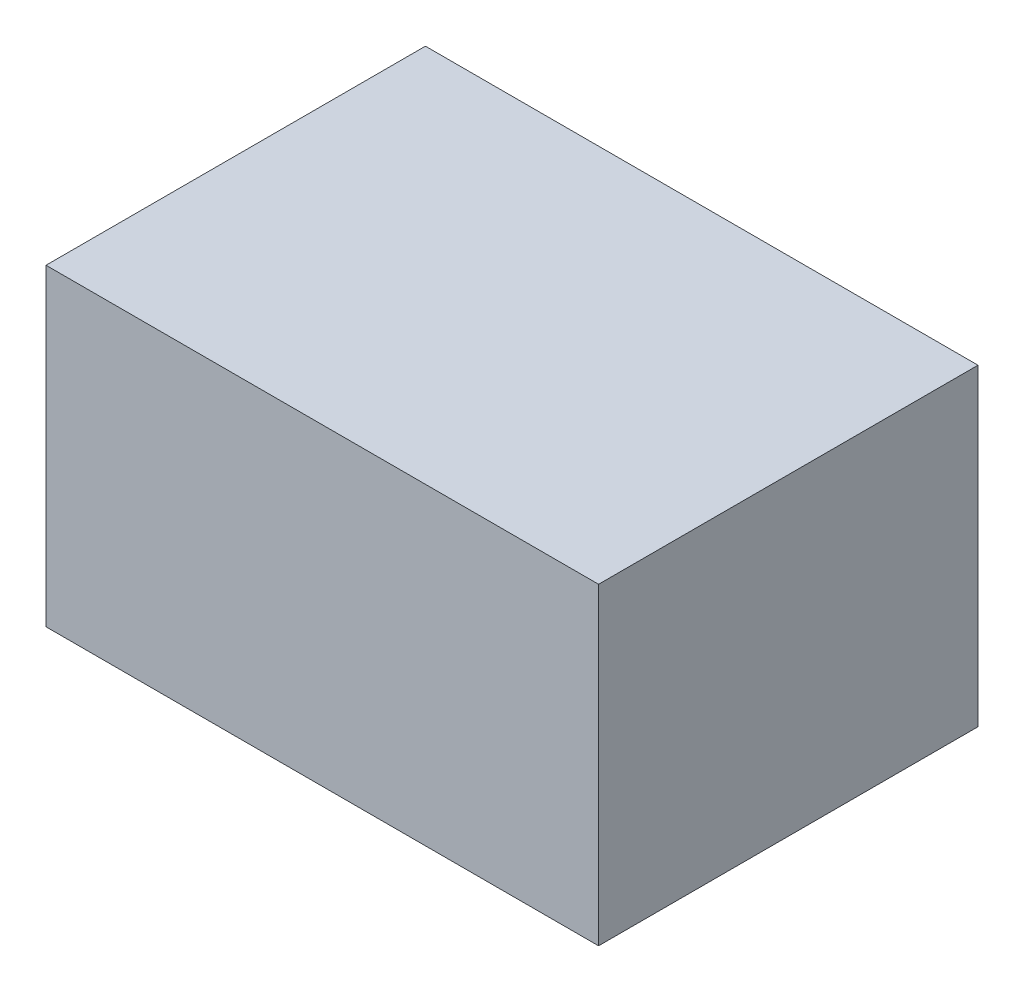
SolidWorks part; units mm, degrees
ref_plane "Спереди" through (0, 0, 0) normal (0, 0, 1) x (1, 0, 0)
ref_plane "Сверху" through (0, 0, 0) normal (0, 1, 0) x (1, 0, 0)
ref_plane "Справа" through (0, 0, 0) normal (1, 0, 0) x (0, 0, -1)
sketch "Sketch1" plane through (0, 0, 0) normal (0, 1, 0) x (1, 0, 0)
  line L1 (-15, -10.3) -> (15, -10.3)
  line L2 (-15, -10.3) -> (-15, 10.3)
  line L3 (-15, 10.3) -> (15, 10.3)
  line L4 (15, -10.3) -> (15, 10.3)
  line L5 (-15, -10.3) -> (15, 10.3) construction
  line L6 (-15, 10.3) -> (15, -10.3) construction
  point P0 (0, 0)
  dimension "D1" = 30
  dimension "D2" = 20.6
extrude "Boss-Extrude1" add sketch "Sketch1" along normal blind 17
